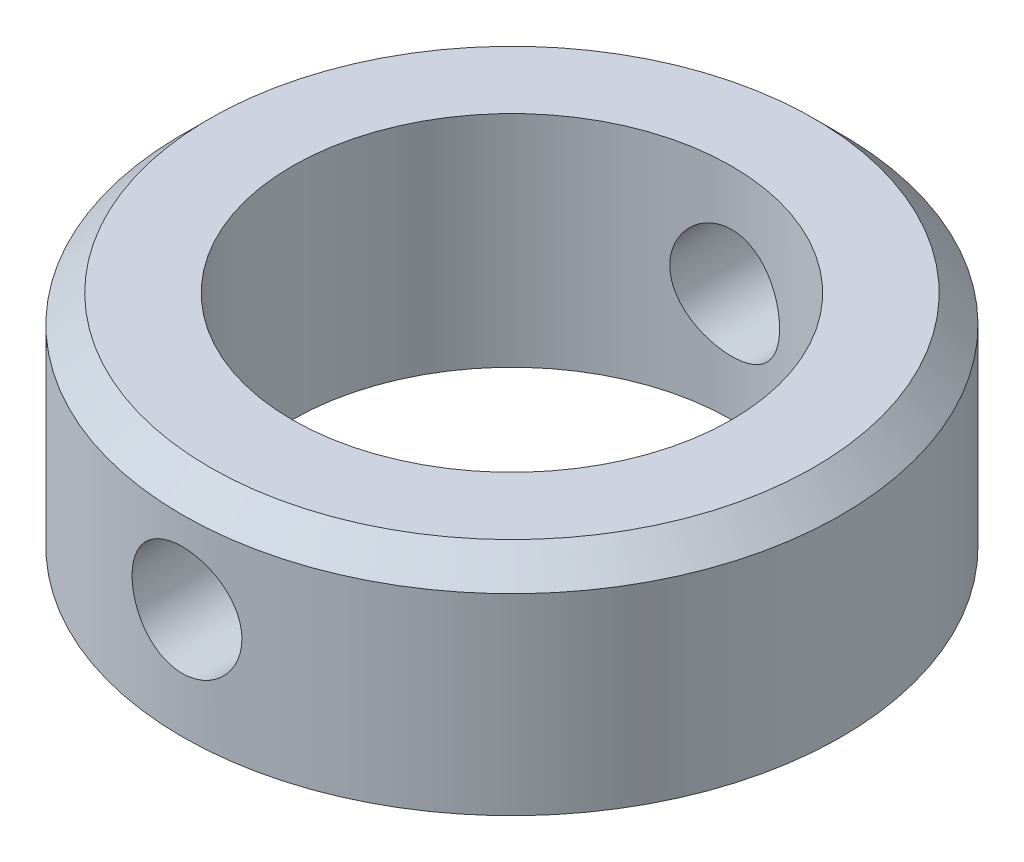
SolidWorks part; units mm, degrees
ref_plane "Front Plane" through (0, 0, 0) normal (0, 0, 1) x (1, 0, 0)
ref_plane "Top Plane" through (0, 0, 0) normal (0, 1, 0) x (1, 0, 0)
ref_plane "Right Plane" through (0, 0, 0) normal (1, 0, 0) x (0, 0, -1)
sketch "Sketch2" plane through (0, 0, 0) normal (0, 1, 0) x (1, 0, 0)
  circle A0 centre (0, 0) radius 12
  circle A1 centre (0, 0) radius 8
extrude "Boss-Extrude1" add sketch "Sketch2" along normal blind 8
sketch "Sketch3" plane through (0, 0, 0) normal (0, 0, 1) x (1, 0, 0)
  line L0 (-12, 0) -> (12, 0) construction
  circle A0 centre (0, 4) radius 2
  dimension "D1" = 4
extrude "Cut-Extrude1" cut sketch "Sketch3" against normal through all both and the other way through all
chamfer "Chamfer1" distance 1 angle 45 1 edges at (0, 8, 12)
